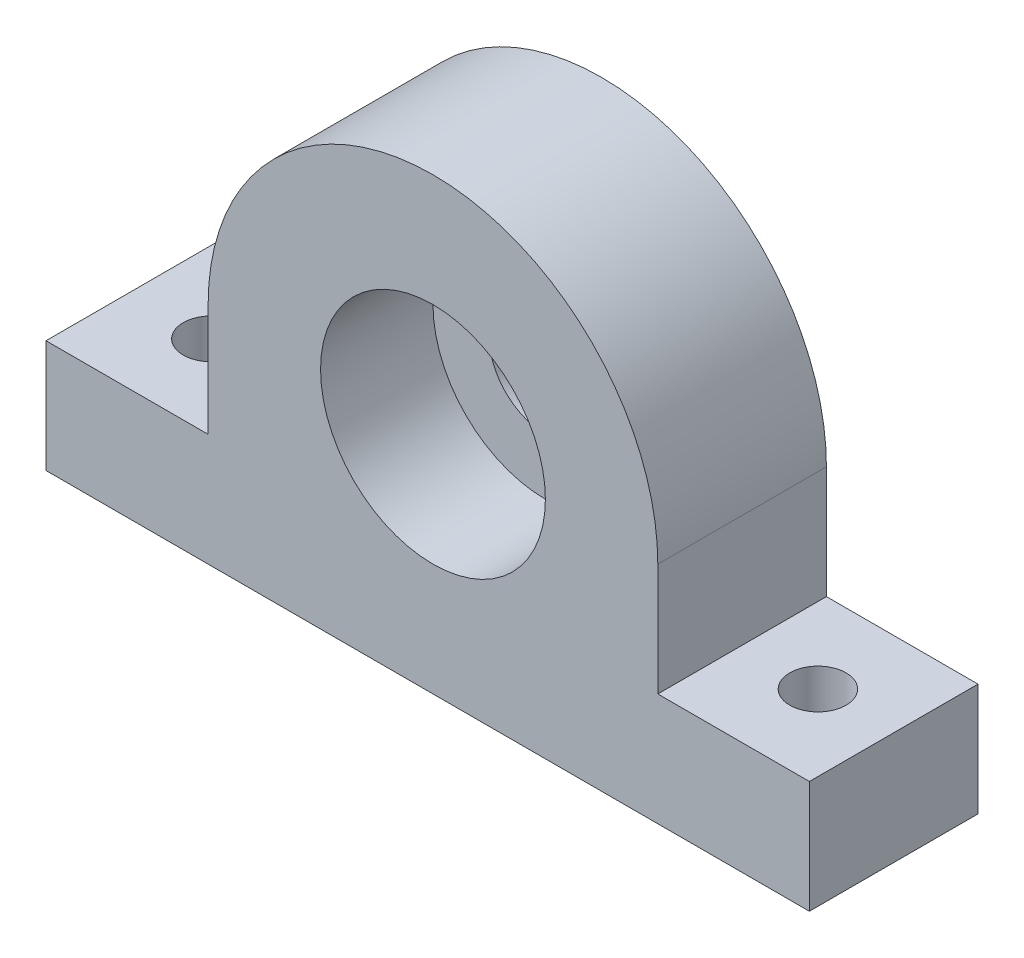
SolidWorks part; units mm, degrees
ref_plane "Front Plane" through (0, 0, 0) normal (0, 0, 1) x (1, 0, 0)
ref_plane "Top Plane" through (0, 0, 0) normal (0, 1, 0) x (1, 0, 0)
ref_plane "Right Plane" through (0, 0, 0) normal (1, 0, 0) x (0, 0, -1)
sketch "Sketch1" plane through (0, 0, 0) normal (0, 0, 1) x (1, 0, 0)
  line L0 (-25.4, 0) -> (25.4, 0)
  line L1 (0, 0) -> (0, 50.8) construction
  line L2 (-25.4, 25.4) -> (-25.4, 0)
  line L3 (25.4, 25.4) -> (25.4, 0)
  line L4 (-34.5584, 12.7) -> (-34.5584, 0) construction
  line L5 (-25.4, 0) -> (-43.7167, 0)
  line L6 (-25.4, 0) -> (-25.4, 12.7)
  line L7 (-25.4, 12.7) -> (-43.7167, 12.7)
  line L8 (-43.7167, 0) -> (-43.7167, 12.7)
  line L9 (25.4, 12.7) -> (42.5231, 12.7)
  line L10 (25.4, 12.7) -> (25.4, 0)
  line L11 (25.4, 0) -> (42.5231, 0)
  line L12 (42.5231, 12.7) -> (42.5231, 0)
  line L13 (33.9615, 12.7) -> (33.9615, 0) construction
  circle A0 centre (0, 25.4) radius 6.35
  arc A1 (25.4, 25.4) -> (-25.4, 25.4) centre (0, 25.4) ccw
  point P4 (0, 0)
  dimension "D1" = 12.7
  dimension "D2" = 25.4
  dimension "D3" = 12.7
extrude "Boss-Extrude1" add sketch "Sketch1" along normal blind 19.05 contours L3 A1 L2 L0 A0 | L8 L5 L2 L7 | L12 L9 L3 L11
sketch "Sketch2" plane through (0, 0, 19.05) normal (0, 0, 1) x (1, 0, 0)
  circle A0 centre (0, 25.4) radius 12.7
  dimension "D1" = 25.4
extrude "Cut-Extrude1" cut sketch "Sketch2" against normal blind 12.7 contours A0
sketch "Sketch3" plane through (0, 12.7, 0) normal (0, 1, 0) x (1, 0, 0)
  line L0 (-43.7167, -9.525) -> (-25.4, -9.525) construction
  line L1 (-43.7167, -19.05) -> (-43.7167, 0) construction
  line L2 (-25.4, -19.05) -> (-25.4, 0) construction
  line L3 (42.5231, -9.525) -> (25.4, -9.525) construction
  line L4 (42.5231, -19.05) -> (42.5231, 0) construction
  line L5 (25.4, -19.05) -> (25.4, 0) construction
  circle A0 centre (-34.5584, -9.525) radius 3.175
  circle A1 centre (33.9615, -9.525) radius 3.175
  dimension "D1" = 6.35
extrude "Cut-Extrude2" cut sketch "Sketch3" against normal up to surface (12.7 mm away) up to face at (-0.5968, 0, 9.525)
